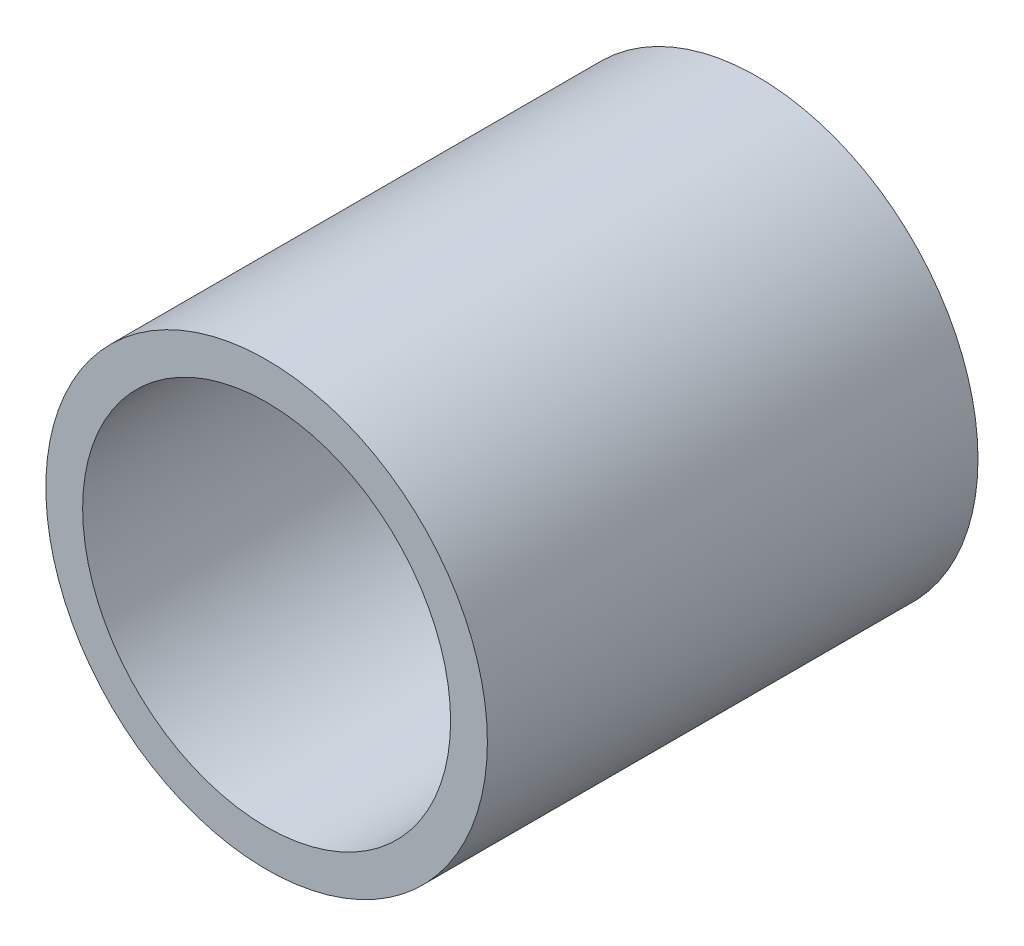
SolidWorks part; units mm, degrees
ref_plane "Front Plane" through (0, 0, 0) normal (0, 0, 1) x (1, 0, 0)
ref_plane "Top Plane" through (0, 0, 0) normal (0, 1, 0) x (1, 0, 0)
ref_plane "Right Plane" through (0, 0, 0) normal (1, 0, 0) x (0, 0, -1)
sketch "Sketch1" plane through (0, 0, 0) normal (0, 0, 1) x (1, 0, 0)
  circle A0 centre (0, 0) radius 45
  circle A1 centre (0, 0) radius 54
  dimension "D1" = 90
  dimension "D2" = 108
extrude "Boss-Extrude1" add sketch "Sketch1" along normal blind 120
sketch "Sketch2" plane through (0, 0, 0) normal (0, 0, -1) x (-1, 0, 0)
  line L0 (0, 0) -> (0, -78) construction
  line L1 (-90.05, -78) -> (90.05, -78)
  line L2 (90.05, -78) -> (90.05, -24.0642)
  line L4 (-57.5, 92.5) -> (-92.5, 92.5)
  line L6 (-65, -60) -> (65, -60) construction
  line L7 (-65, -60) -> (-65, 70) construction
  line L8 (-65, 70) -> (-75, 70) construction
  line L9 (-85.05, -73) -> (-44.95, -73)
  line L10 (-85.05, -73) -> (-85.05, -47)
  line L11 (-85.05, -47) -> (-44.95, -47)
  line L12 (-44.95, -73) -> (-44.95, -47)
  line L13 (-85.05, -73) -> (-44.95, -47) construction
  line L14 (-85.05, -47) -> (-44.95, -73) construction
  line L15 (44.95, -73) -> (85.05, -73)
  line L16 (44.95, -73) -> (44.95, -47)
  line L17 (44.95, -47) -> (85.05, -47)
  line L18 (85.05, -73) -> (85.05, -47)
  line L19 (44.95, -73) -> (85.05, -47) construction
  line L20 (44.95, -47) -> (85.05, -73) construction
  line L25 (-92.5, 92.5) -> (-92.5, 12.8481)
  line L26 (-87.5, 87.5) -> (-62.5, 87.5)
  line L27 (-87.5, 87.5) -> (-87.5, 52.5)
  line L28 (-87.5, 52.5) -> (-62.5, 52.5)
  line L29 (-62.5, 87.5) -> (-62.5, 52.5)
  line L30 (-87.5, 87.5) -> (-62.5, 52.5) construction
  line L31 (-87.5, 52.5) -> (-62.5, 87.5) construction
  line L32 (-90.05, -78) -> (-90.05, 5.34)
  line L33 (-90.05, 5.34) -> (-92.5, 12.8481)
  line L34 (90.05, -24.0642) -> (49.7813, 20.9241)
  line L35 (-57.5, 92.5) -> (-11.8863, 52.6756)
  circle A0 centre (0, 0) radius 54 construction
  point P6 (0, -78)
  point P12 (0, -60)
  point P29 (49.7813, 20.9241)
  point P30 (-11.8863, 52.6756)
  dimension "D1" = 130
  dimension "D2" = 60
  dimension "D3" = 130
  dimension "D4" = 5
  dimension "D5" = 26
  dimension "D6" = 40.1
  dimension "D7" = 40.1
  dimension "D8" = 26
  dimension "D9" = 5
  dimension "D10" = 10
  dimension "D11" = 25
  dimension "D12" = 35
  dimension "D13" = 5
  dimension "D14" = 5
  dimension "D15" = 35
